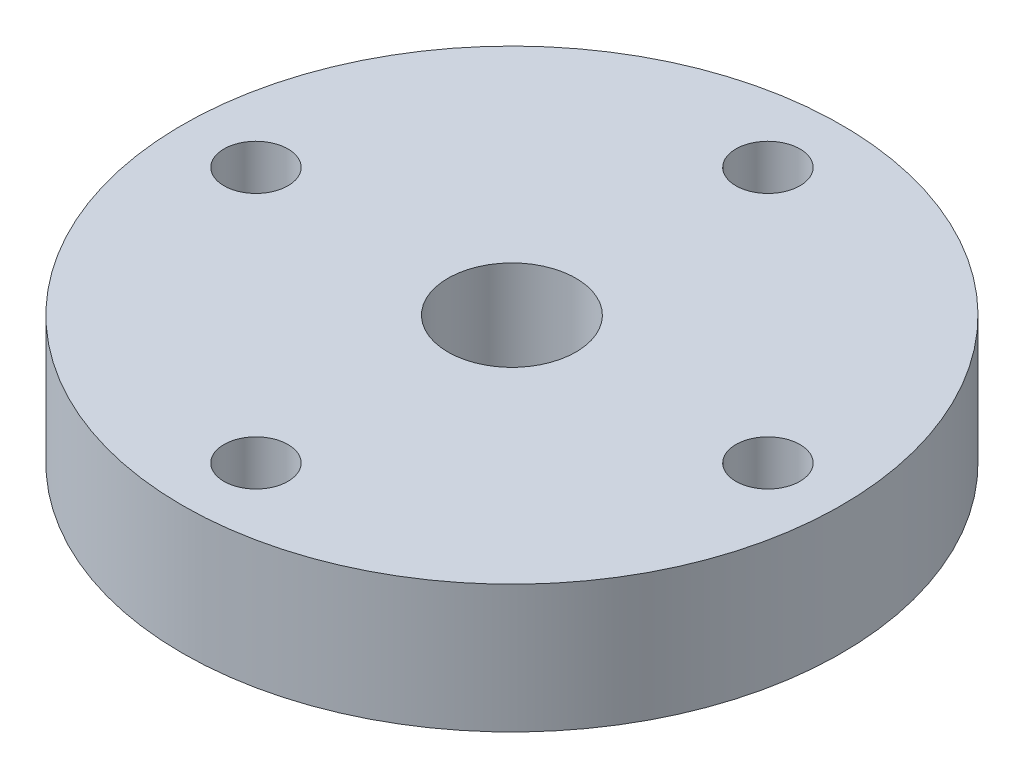
SolidWorks part; units mm, degrees
ref_plane "Front Plane" through (0, 0, 0) normal (0, 0, 1) x (1, 0, 0)
ref_plane "Top Plane" through (0, 0, 0) normal (0, 1, 0) x (1, 0, 0)
ref_plane "Right Plane" through (0, 0, 0) normal (1, 0, 0) x (0, 0, -1)
sketch "Sketch1" plane through (0, 0, 0) normal (0, 1, 0) x (1, 0, 0)
  circle A0 centre (0, 0) radius 10.3
  circle A1 centre (0, 0) radius 2
extrude "Boss-Extrude1" add sketch "Sketch1" along normal blind 4
sketch "Sketch2" plane through (0, 4, 0) normal (0, 1, 0) x (-1, 0, 0)
  circle A0 centre (0, -8) radius 1
  circle A1 centre (8, 0) radius 1
  circle A2 centre (-8, 0) radius 1
  circle A3 centre (0, 8) radius 1
  point P0 (0, 0)
  point P1 (0, -8)
  point P5 (8, 0)
  point P6 (-8, 0)
  point P7 (0, 8)
  dimension "D2" = 8
  dimension "D1" = 8
  dimension "D3" = 8
  dimension "D4" = 8
extrude "Cut-Extrude1" cut sketch "Sketch2" against normal blind 4
sketch "Sketch3" plane through (0, 0, 0) normal (0, -1, 0) x (1, 0, 0)
  circle A0 centre (0, 0) radius 4.25
  circle A1 centre (0, 0) radius 6
extrude "Cut-Extrude2" cut sketch "Sketch3" against normal blind 2
